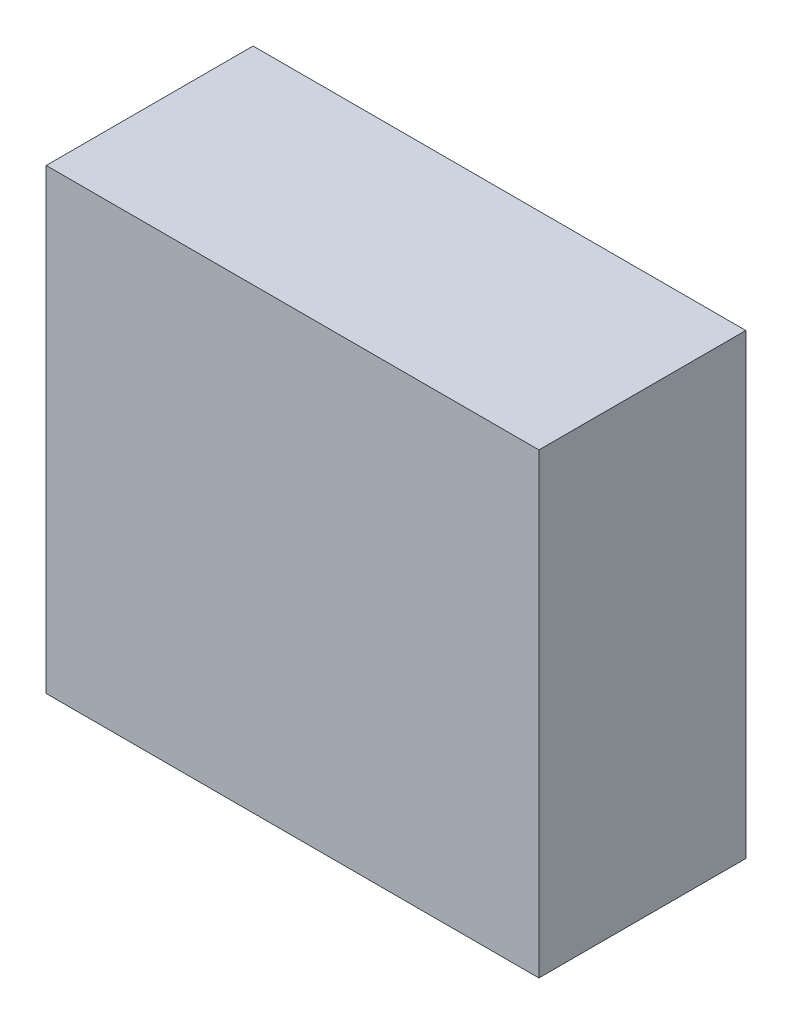
SolidWorks part; units mm, degrees
ref_plane "Front Plane" through (0, 0, 0) normal (0, 0, 1) x (1, 0, 0)
ref_plane "Top Plane" through (0, 0, 0) normal (0, 1, 0) x (1, 0, 0)
ref_plane "Right Plane" through (0, 0, 0) normal (1, 0, 0) x (0, 0, -1)
sketch "Sketch1" plane through (0, 0, 0) normal (0, 1, 0) x (1, 0, 0)
  line L1 (90.5, -38) -> (-90.5, -38)
  line L2 (90.5, -38) -> (90.5, 38)
  line L3 (90.5, 38) -> (-90.5, 38)
  line L4 (-90.5, -38) -> (-90.5, 38)
  line L5 (90.5, -38) -> (-90.5, 38) construction
  line L6 (90.5, 38) -> (-90.5, -38) construction
  point P0 (0, 0)
  dimension "D1" = 181
  dimension "D2" = 76
extrude "Boss-Extrude1" add sketch "Sketch1" along normal blind 168
